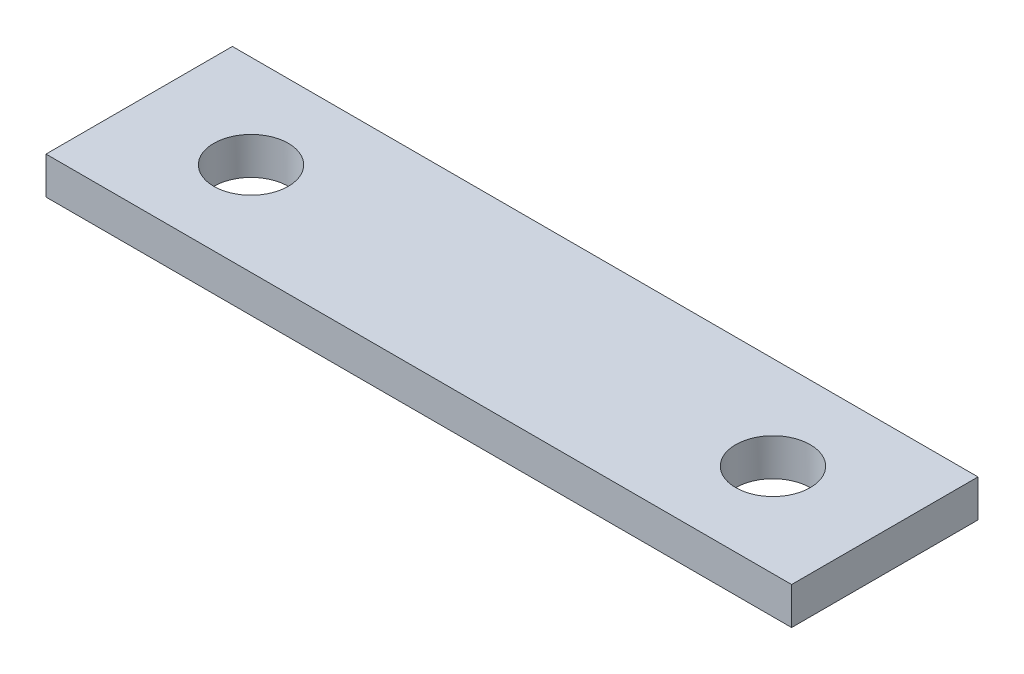
SolidWorks part; units mm, degrees
ref_plane "Front Plane" through (0, 0, 0) normal (0, 0, 1) x (1, 0, 0)
ref_plane "Top Plane" through (0, 0, 0) normal (0, 1, 0) x (1, 0, 0)
ref_plane "Right Plane" through (0, 0, 0) normal (1, 0, 0) x (0, 0, -1)
sketch "Sketch2" plane through (0, 0, 0) normal (0, 1, 0) x (1, 0, 0)
  line L1 (-5, -1.25) -> (5, -1.25)
  line L2 (-5, -1.25) -> (-5, 1.25)
  line L3 (-5, 1.25) -> (5, 1.25)
  line L4 (5, -1.25) -> (5, 1.25)
  line L5 (-5, -1.25) -> (5, 1.25) construction
  line L6 (-5, 1.25) -> (5, -1.25) construction
  point P0 (0, 0)
  dimension "D1" = 2.5
  dimension "D2" = 10
extrude "Boss-Extrude1" add sketch "Sketch2" along normal blind 0.5
sketch "Sketch3" plane through (0, 0.5, 0) normal (0, 1, 0) x (1, 0, 0)
  circle A0 centre (-3.5, 0) radius 0.5
  circle A1 centre (3.5, 0) radius 0.5
  dimension "D1" = 1
  dimension "D2" = 3.5
  dimension "D3" = 3.5
extrude "Cut-Extrude1" cut sketch "Sketch3" against normal through all both and the other way through all
